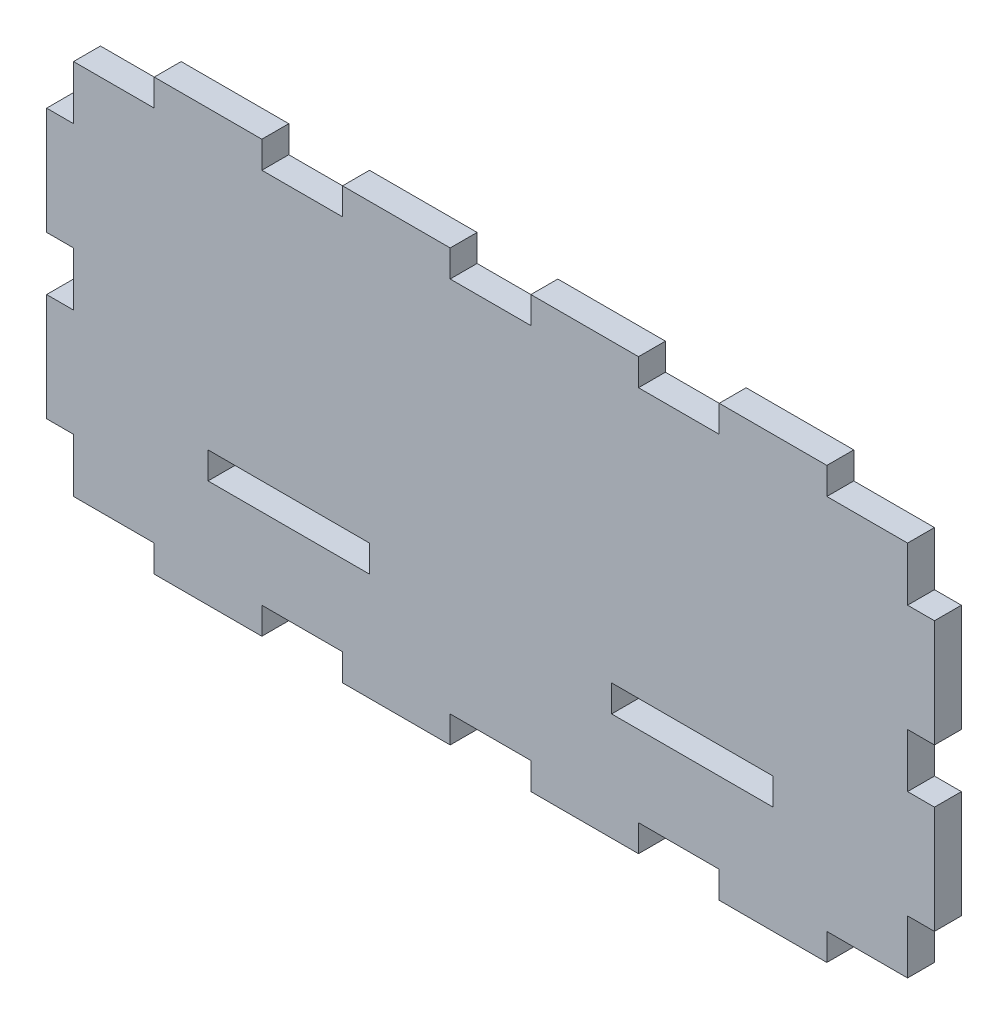
SolidWorks part; units mm, degrees
ref_plane "Front Plane" through (0, 0, 0) normal (0, 0, 1) x (1, 0, 0)
ref_plane "Top Plane" through (0, 0, 0) normal (0, 1, 0) x (1, 0, 0)
ref_plane "Right Plane" through (0, 0, 0) normal (1, 0, 0) x (0, 0, -1)
sketch "Sketch1" plane through (0, 0, 0) normal (0, 0, 1) x (1, 0, 0)
  line L0 (-102.5487, 0) -> (106.5223, 0) construction
  line L1 (1.9868, -67.8564) -> (1.9868, 74.8865) construction
  line L2 (-75.5132, 35) -> (-60.5132, 35)
  line L3 (-75.5132, 35) -> (79.4868, 35) construction
  line L4 (-75.5132, 35) -> (-75.5132, -35) construction
  line L5 (-75.5132, -35) -> (79.4868, -35) construction
  line L6 (79.4868, 35) -> (79.4868, -35) construction
  line L7 (-75.5132, 35) -> (79.4868, -35) construction
  line L8 (-75.5132, -35) -> (79.4868, 35) construction
  line L9 (-60.5132, 35) -> (-60.5132, 40)
  line L10 (-60.5132, 40) -> (-40.5132, 40)
  line L11 (-40.5132, 40) -> (-40.5132, 35)
  line L12 (-25.5132, 35) -> (-25.5132, 40)
  line L13 (-25.5132, 40) -> (-5.5132, 40)
  line L14 (-5.5132, 40) -> (-5.5132, 35)
  line L15 (-40.5132, 35) -> (-25.5132, 35)
  line L16 (9.4868, 35) -> (9.4868, 40)
  line L17 (9.4868, 40) -> (29.4868, 40)
  line L18 (29.4868, 40) -> (29.4868, 35)
  line L19 (-5.5132, 35) -> (9.4868, 35)
  line L20 (44.4868, 35) -> (44.4868, 40)
  line L21 (44.4868, 40) -> (64.4868, 40)
  line L22 (64.4868, 40) -> (64.4868, 35)
  line L23 (29.4868, 35) -> (44.4868, 35)
  line L24 (64.4868, -35) -> (79.4868, -35)
  line L25 (29.4868, -35) -> (44.4868, -35)
  line L26 (64.4868, -40) -> (64.4868, -35)
  line L27 (64.4868, 35) -> (79.4868, 35)
  line L28 (79.4868, 40) -> (99.4868, 40) [skipped]
  line L29 (99.4868, 40) -> (99.4868, 35) [skipped]
  line L30 (79.4868, 35) -> (79.4868, 40) [skipped]
  line L31 (44.4868, -40) -> (64.4868, -40)
  line L32 (44.4868, -35) -> (44.4868, -40)
  line L33 (-5.5132, -35) -> (9.4868, -35)
  line L34 (29.4868, -40) -> (29.4868, -35)
  line L35 (9.4868, -40) -> (29.4868, -40)
  line L36 (9.4868, -35) -> (9.4868, -40)
  line L37 (-40.5132, -35) -> (-25.5132, -35)
  line L38 (-5.5132, -40) -> (-5.5132, -35)
  line L39 (-25.5132, -40) -> (-5.5132, -40)
  line L40 (-25.5132, -35) -> (-25.5132, -40)
  line L41 (-40.5132, -40) -> (-40.5132, -35)
  line L42 (-60.5132, -40) -> (-40.5132, -40)
  line L43 (-60.5132, -35) -> (-60.5132, -40)
  line L44 (-75.5132, -35) -> (-60.5132, -35)
  line L45 (-75.5132, 35) -> (-75.5132, 25)
  line L46 (-75.5132, 25) -> (-80.5132, 25)
  line L47 (-80.5132, 25) -> (-80.5132, 5)
  line L48 (-80.5132, 5) -> (-75.5132, 5)
  line L49 (-75.5132, 5) -> (-75.5132, -5)
  line L50 (-75.5132, -5) -> (-80.5132, -5)
  line L51 (-80.5132, -5) -> (-80.5132, -25)
  line L52 (-80.5132, -25) -> (-75.5132, -25)
  line L53 (-75.5132, -25) -> (-75.5132, -35)
  line L54 (79.4868, -25) -> (79.4868, -35)
  line L55 (84.4868, -25) -> (79.4868, -25)
  line L56 (84.4868, -5) -> (84.4868, -25)
  line L57 (79.4868, -5) -> (84.4868, -5)
  line L58 (79.4868, 5) -> (79.4868, -5)
  line L59 (84.4868, 5) -> (79.4868, 5)
  line L60 (84.4868, 25) -> (84.4868, 5)
  line L61 (79.4868, 25) -> (84.4868, 25)
  line L62 (79.4868, 35) -> (79.4868, 25)
  point P5 (1.9868, 0)
  dimension "D1" = 70
  dimension "D2" = 155
  dimension "D3" = 5
extrude "Boss-Extrude1" add sketch "Sketch1" along normal blind 5 contours L62 L27 L22 L21 L20 L23 L18 L17 L16 L19 L14 L13 L12 L15 L11 L10 L9 L2 L45 L46 L47 L48 L49 L50 L51 L52 L53 L44 L43 L42 L41 L37 L40 L39 L38 L33 L36 L35 L34 L25 L32 L31 L26 L24 L54 L55 L56 L57 L58 L59 L60
sketch "Sketch2" plane through (0, 0, 5) normal (0, 0, 1) x (1, 0, 0)
  line L0 (-75.5132, -20) -> (79.4868, -20) construction
  line L1 (-75.5132, -25) -> (-75.5132, -35) construction
  line L2 (79.4868, -25) -> (79.4868, -35) construction
  line L3 (-40.5132, -35) -> (-25.5132, -35) construction
  line L4 (-75.5132, -5) -> (-75.5132, -25) construction
  line L5 (79.4868, -5) -> (79.4868, -25) construction
  line L6 (1.9868, 17.1835) -> (1.9868, -28.6391) construction
  line L7 (54.4868, -15) -> (54.4868, -20)
  line L8 (24.4868, -15) -> (54.4868, -15)
  line L9 (54.4868, -20) -> (24.4868, -20)
  line L10 (24.4868, -20) -> (24.4868, -15)
  line L11 (-50.5132, -20) -> (-20.5132, -20)
  line L12 (-50.5132, -15) -> (-50.5132, -20)
  line L13 (-20.5132, -15) -> (-50.5132, -15)
  line L14 (-20.5132, -20) -> (-20.5132, -15)
  point P27 (-50.5132, -17.5)
  dimension "D3" = 25
  dimension "D1" = 155
  dimension "D2" = 15
extrude "Cut-Extrude1" cut sketch "Sketch2" against normal up to surface (5 mm away) up to face at (1.9868, 0, 0)
